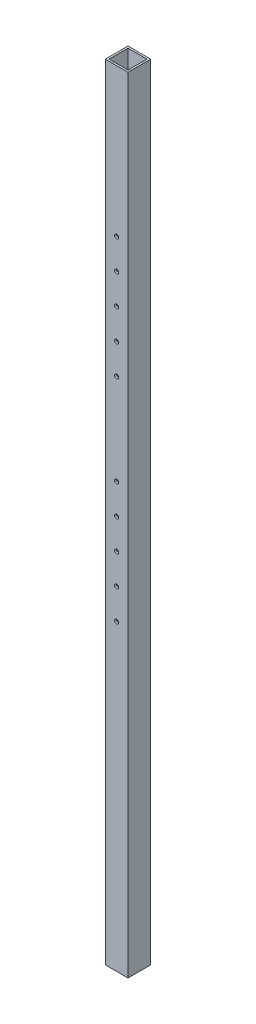
SolidWorks part; units mm, degrees
ref_plane "Front Plane" through (0, 0, 0) normal (0, 0, 1) x (1, 0, 0)
ref_plane "Top Plane" through (0, 0, 0) normal (0, 1, 0) x (1, 0, 0)
ref_plane "Right Plane" through (0, 0, 0) normal (1, 0, 0) x (0, 0, -1)
sketch "Sketch1" plane through (0, 0, 0) normal (0, 1, 0) x (0, 0, 1)
  line L1 (-9.525, 9.525) -> (9.525, 9.525)
  line L2 (-9.525, 9.525) -> (-9.525, -9.525)
  line L3 (-9.525, -9.525) -> (9.525, -9.525)
  line L4 (9.525, 9.525) -> (9.525, -9.525)
  line L5 (-9.525, 9.525) -> (9.525, -9.525) construction
  line L6 (-9.525, -9.525) -> (9.525, 9.525) construction
  line L7 (-7.9375, 7.9375) -> (7.9375, 7.9375)
  line L8 (-7.9375, 7.9375) -> (-7.9375, -7.9375)
  line L9 (-7.9375, -7.9375) -> (7.9375, -7.9375)
  line L10 (7.9375, 7.9375) -> (7.9375, -7.9375)
  line L11 (-7.9375, 7.9375) -> (7.9375, -7.9375) construction
  line L12 (-7.9375, -7.9375) -> (7.9375, 7.9375) construction
  point P0 (0, 0)
  point P5 (0, 0)
  dimension "D1" = 15.875
  dimension "D2" = 19.05
extrude "Boss-Extrude1" add sketch "Sketch1" along normal mid plane 657.3266
sketch "Sketch2" plane through (0, 0, 9.525) normal (0, 0, 1) x (1, 0, 0)
  line L0 (0, 0) -> (0, -74.6633) construction
  line L1 (-9.525, -328.6633) -> (9.525, -328.6633) construction
  circle A0 centre (0, -74.6633) radius 1.7145
  dimension "D1" = 3.429
  dimension "D2" = 254
extrude "Cut-Extrude1" cut sketch "Sketch2" against normal through all
pattern_linear "LPattern1" count 5 spacing 25.4 along (0, 1, 0) of "Cut-Extrude1"
pattern_linear "LPattern2" count 2 spacing 177.8 along (0, 1, 0) of "LPattern1", "Cut-Extrude1"
